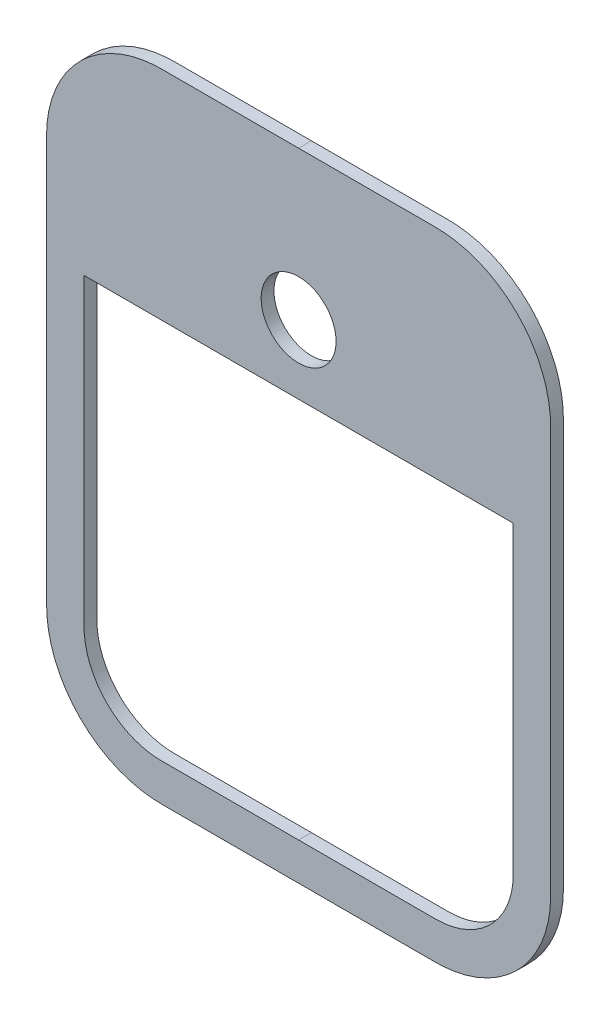
SolidWorks part; units mm, degrees
material "Фанера"
ref_plane "Front Plane" through (0, 0, 0) normal (0, 0, 1) x (1, 0, 0)
ref_plane "Top Plane" through (0, 0, 0) normal (0, 1, 0) x (1, 0, 0)
ref_plane "Right Plane" through (0, 0, 0) normal (1, 0, 0) x (0, 0, -1)
sketch "Эскиз1" plane through (0, 0, 0) normal (0, 0, 1) x (1, 0, 0)
  line L0 (-47, 88.5735) -> (47, 88.5735)
  circle A1 centre (0, 103.6369) radius 5.3081 construction
  circle A2 centre (0, 103.6369) radius 8.2
  spline S2 degree 3 poles (0, -3.0157) (10, -3.0157) (20, -3.0157) (31.6362, -3.0157) (34.9087, -2.6935) (39.6288, -1.2616) (43.9788, 1.0635) (47.7917, 4.1926) (50.9208, 8.0055) (53.2459, 12.3555) (54.6778, 17.0756) (55, 20.3481) (55, 51.6579) (55, 81.3315) (55, 112.6414) (54.6778, 115.9139) (53.2459, 120.6339) (50.9208, 124.984) (47.7917, 128.7968) (43.9788, 131.926) (39.6288, 134.2511) (34.9087, 135.6829) (31.6362, 136.0052) (20, 136.0052) (10, 136.0052) (0, 136.0052) knots 0 0 0 0 0.131833 0.131833 0.153404 0.174975 0.196546 0.218117 0.239689 0.26126 0.282831 0.304402 0.304402 0.695598 0.695598 0.717169 0.73874 0.760311 0.781883 0.803454 0.825025 0.846596 0.868167 0.868167 1 1 1 1 construction
  spline S3 degree 3 poles (0, 136.0052) (-10, 136.0052) (-20, 136.0052) (-31.6362, 136.0052) (-34.9087, 135.6829) (-39.6288, 134.2511) (-43.9788, 131.926) (-47.7917, 128.7968) (-50.9208, 124.984) (-53.2459, 120.6339) (-54.6778, 115.9139) (-55, 112.6414) (-55, 81.3315) (-55, 51.6579) (-55, 20.3481) (-54.6778, 17.0756) (-53.2459, 12.3555) (-50.9208, 8.0055) (-47.7917, 4.1926) (-43.9788, 1.0635) (-39.6288, -1.2616) (-34.9087, -2.6935) (-31.6362, -3.0157) (-20, -3.0157) (-10, -3.0157) (0, -3.0157) knots 0 0 0 0 0.131833 0.131833 0.153404 0.174975 0.196546 0.218117 0.239689 0.26126 0.282831 0.304402 0.304402 0.695598 0.695598 0.717169 0.73874 0.760311 0.781883 0.803454 0.825025 0.846596 0.868167 0.868167 1 1 1 1 construction
  spline S4 degree 1 poles (0, 136.2052) (0, -3.2157) knots 0 0 1 1 construction
  spline S5 degree 1 poles (0, -3.2157) (0, 136.2052) knots 0 0 1 1 construction
  spline S6 degree 3 poles (0, 136.2052) (-2.3704, 136.2052) (-7.1112, 136.2051) (-14.2228, 136.2054) (-20.1479, 136.2046) (-24.8907, 136.2062) (-28.4404, 136.2012) (-32.0181, 136.22) (-35.5745, 135.6656) (-39.013, 134.63) (-43.357, 132.6076) (-48.1651, 128.9623) (-51.755, 124.1125) (-53.7267, 119.7454) (-54.724, 116.2955) (-55.2324, 112.732) (-55.1913, 109.1586) (-55.2023, 105.6077) (-55.1987, 100.8653) (-55.2004, 94.94) (-55.1999, 87.8285) (-55.2001, 78.3469) (-55.2, 66.4947) (-55.2001, 54.6426) (-55.1999, 45.161) (-55.2004, 38.0495) (-55.1987, 32.1242) (-55.2023, 27.3818) (-55.1913, 23.8308) (-55.2324, 20.2575) (-54.724, 16.694) (-53.7267, 13.2441) (-51.755, 8.8769) (-48.1651, 4.0272) (-43.357, 0.3819) (-39.013, -1.6405) (-35.5745, -2.6761) (-32.0181, -3.2305) (-28.4404, -3.2117) (-24.8907, -3.2167) (-20.1479, -3.2151) (-14.2228, -3.2159) (-7.1112, -3.2156) (-2.3704, -3.2157) (0, -3.2157) knots 0 0 0 0 0.03125 0.0625 0.09375 0.109375 0.125 0.140625 0.15625 0.171875 0.1875 0.21875 0.25 0.265625 0.28125 0.296875 0.3125 0.328125 0.34375 0.375 0.40625 0.4375 0.5 0.5625 0.59375 0.625 0.65625 0.671875 0.6875 0.703125 0.71875 0.734375 0.75 0.78125 0.8125 0.828125 0.84375 0.859375 0.875 0.890625 0.90625 0.9375 0.96875 1 1 1 1
  spline S7 degree 3 poles (0, -3.2157) (2.3704, -3.2157) (7.1112, -3.2156) (14.2228, -3.2159) (20.1479, -3.2151) (24.8907, -3.2167) (28.4404, -3.2117) (32.0181, -3.2305) (35.5745, -2.6761) (39.013, -1.6405) (43.357, 0.3819) (48.1651, 4.0272) (51.755, 8.8769) (53.7267, 13.2441) (54.724, 16.694) (55.2324, 20.2575) (55.1913, 23.8308) (55.2023, 27.3818) (55.1987, 32.1242) (55.2004, 38.0495) (55.1999, 45.161) (55.2001, 54.6426) (55.2, 66.4947) (55.2001, 78.3469) (55.1999, 87.8285) (55.2004, 94.94) (55.1987, 100.8653) (55.2023, 105.6077) (55.1913, 109.1586) (55.2324, 112.732) (54.724, 116.2955) (53.7267, 119.7454) (51.755, 124.1125) (48.1651, 128.9623) (43.357, 132.6076) (39.013, 134.63) (35.5745, 135.6656) (32.0181, 136.22) (28.4404, 136.2012) (24.8907, 136.2062) (20.1479, 136.2046) (14.2228, 136.2054) (7.1112, 136.2051) (2.3704, 136.2052) (0, 136.2052) knots 0 0 0 0 0.03125 0.0625 0.09375 0.109375 0.125 0.140625 0.15625 0.171875 0.1875 0.21875 0.25 0.265625 0.28125 0.296875 0.3125 0.328125 0.34375 0.375 0.40625 0.4375 0.5 0.5625 0.59375 0.625 0.65625 0.671875 0.6875 0.703125 0.71875 0.734375 0.75 0.78125 0.8125 0.828125 0.84375 0.859375 0.875 0.890625 0.90625 0.9375 0.96875 1 1 1 1
  spline S8 degree 1 poles (0, 128.0052) (0, 4.9843) knots 0 0 1 1 construction
  spline S9 degree 1 poles (0, 4.9843) (0, 128.0052) knots 0 0 1 1 construction
  spline S10 degree 3 poles (0, 128.0052) (-2.3704, 128.0052) (-7.1113, 128.0052) (-13.0373, 128.0052) (-17.7782, 128.0052) (-20.7411, 128.0052) (-23.1118, 128.0052) (-24.8889, 128.0052) (-26.6692, 128.0052) (-28.1432, 128.0051) (-29.1936, 128.0052) (-29.6934, 128.0051) (-30.02, 128.0053) (-30.1904, 128.0046) (-30.4571, 128) (-30.8539, 127.9857) (-31.3599, 127.9543) (-31.9612, 127.8952) (-32.7609, 127.788) (-34.1451, 127.5265) (-36.0814, 126.9418) (-39.0103, 125.5784) (-42.2541, 123.1194) (-44.6763, 119.8468) (-46.0055, 116.9027) (-46.568, 114.9601) (-46.8135, 113.5726) (-46.9115, 112.7716) (-46.9636, 112.1695) (-46.9892, 111.6641) (-46.9977, 111.3153) (-46.9996, 111.1342) (-47, 111.0417) (-47, 110.8408) (-47, 110.4912) (-47, 109.9057) (-47, 109.1615) (-47, 108.2737) (-47, 107.0881) (-47, 105.0142) (-47, 102.0511) (-47, 98.4955) (-47, 94.2992) (-47, 90.6956) (-47, 85.9548) (-47, 80.6693) (-47, 73.606) (-47, 66.4947) (-47, 59.3835) (-47, 52.2722) (-47, 45.1609) (-47, 39.2349) (-47, 34.494) (-47, 30.9384) (-47, 27.9753) (-47, 25.9014) (-47, 24.7158) (-47, 23.828) (-47, 23.0837) (-47, 22.4982) (-47, 22.1486) (-47, 21.9478) (-46.9996, 21.8553) (-46.9977, 21.6741) (-46.9892, 21.3254) (-46.9636, 20.82) (-46.9115, 20.2179) (-46.8135, 19.4169) (-46.568, 18.0294) (-46.0055, 16.0868) (-44.6763, 13.1427) (-42.2541, 9.87) (-39.0103, 7.411) (-36.0814, 6.0477) (-34.1451, 5.4629) (-32.7609, 5.2015) (-31.9612, 5.0943) (-31.3599, 5.0352) (-30.8539, 5.0038) (-30.4571, 4.9895) (-30.1904, 4.9849) (-30.02, 4.9842) (-29.6934, 4.9844) (-29.1936, 4.9843) (-28.1432, 4.9843) (-26.6692, 4.9843) (-24.8889, 4.9843) (-23.1118, 4.9843) (-20.7411, 4.9843) (-17.7782, 4.9843) (-13.0373, 4.9843) (-7.1113, 4.9843) (-2.3704, 4.9843) (0, 4.9843) knots 0 0 0 0 0.03125 0.0625 0.078125 0.09375 0.101562 0.109375 0.117188 0.125 0.128906 0.130859 0.131836 0.132812 0.134766 0.136719 0.140625 0.144531 0.148438 0.15625 0.171875 0.1875 0.21875 0.25 0.265625 0.28125 0.289062 0.292969 0.296875 0.300781 0.302734 0.303711 0.304199 0.304688 0.306641 0.308594 0.3125 0.316406 0.320312 0.328125 0.34375 0.359375 0.375 0.39907 0.406882 0.4375 0.46875 0.5 0.53125 0.5625 0.59375 0.625 0.640625 0.65625 0.671875 0.679688 0.683594 0.6875 0.691406 0.693359 0.695312 0.695801 0.696289 0.697266 0.699219 0.703125 0.707031 0.710938 0.71875 0.734375 0.75 0.78125 0.8125 0.828125 0.84375 0.851562 0.855469 0.859375 0.863281 0.865234 0.867188 0.868164 0.869141 0.871094 0.875 0.882812 0.890625 0.898438 0.90625 0.921875 0.9375 0.96875 1 1 1 1
  spline S11 degree 3 poles (0, 4.9843) (2.3704, 4.9843) (7.1113, 4.9843) (13.0373, 4.9843) (17.7782, 4.9843) (20.7411, 4.9843) (23.1118, 4.9843) (24.8889, 4.9843) (26.6692, 4.9843) (28.1432, 4.9843) (29.1936, 4.9843) (29.6934, 4.9844) (30.02, 4.9842) (30.1904, 4.9849) (30.4571, 4.9895) (30.8539, 5.0038) (31.3599, 5.0352) (31.9612, 5.0943) (32.7609, 5.2015) (34.1451, 5.4629) (36.0814, 6.0477) (39.0103, 7.411) (42.2541, 9.87) (44.6763, 13.1427) (46.0055, 16.0868) (46.568, 18.0294) (46.8135, 19.4169) (46.9115, 20.2179) (46.9636, 20.82) (46.9892, 21.3254) (46.9977, 21.6741) (46.9996, 21.8553) (47, 21.9478) (47, 22.1486) (47, 22.4982) (47, 23.0837) (47, 23.828) (47, 24.7158) (47, 25.9014) (47, 27.9753) (47, 30.9384) (47, 34.494) (47, 39.2349) (47, 45.1609) (47, 52.2722) (47, 59.3835) (47, 66.4947) (47, 73.606) (47, 80.6693) (47, 85.9548) (47, 90.6956) (47, 94.2992) (47, 98.4955) (47, 102.0511) (47, 105.0142) (47, 107.0881) (47, 108.2737) (47, 109.1615) (47, 109.9057) (47, 110.4912) (47, 110.8408) (47, 111.0417) (46.9996, 111.1342) (46.9977, 111.3153) (46.9892, 111.6641) (46.9636, 112.1695) (46.9115, 112.7716) (46.8135, 113.5726) (46.568, 114.9601) (46.0055, 116.9027) (44.6763, 119.8468) (42.2541, 123.1194) (39.0103, 125.5784) (36.0814, 126.9418) (34.1451, 127.5265) (32.7609, 127.788) (31.9612, 127.8952) (31.3599, 127.9543) (30.8539, 127.9857) (30.4571, 128) (30.1904, 128.0046) (30.02, 128.0053) (29.6934, 128.0051) (29.1936, 128.0052) (28.1432, 128.0051) (26.6692, 128.0052) (24.8889, 128.0052) (23.1118, 128.0052) (20.7411, 128.0052) (17.7782, 128.0052) (13.0373, 128.0052) (7.1113, 128.0052) (2.3704, 128.0052) (0, 128.0052) knots 0 0 0 0 0.03125 0.0625 0.078125 0.09375 0.101562 0.109375 0.117188 0.125 0.128906 0.130859 0.131836 0.132812 0.134766 0.136719 0.140625 0.144531 0.148438 0.15625 0.171875 0.1875 0.21875 0.25 0.265625 0.28125 0.289062 0.292969 0.296875 0.300781 0.302734 0.303711 0.304199 0.304688 0.306641 0.308594 0.3125 0.316406 0.320312 0.328125 0.34375 0.359375 0.375 0.40625 0.4375 0.46875 0.5 0.53125 0.5625 0.593118 0.60093 0.625 0.640625 0.65625 0.671875 0.679688 0.683594 0.6875 0.691406 0.693359 0.695312 0.695801 0.696289 0.697266 0.699219 0.703125 0.707031 0.710938 0.71875 0.734375 0.75 0.78125 0.8125 0.828125 0.84375 0.851562 0.855469 0.859375 0.863281 0.865234 0.867188 0.868164 0.869141 0.871094 0.875 0.882812 0.890625 0.898438 0.90625 0.921875 0.9375 0.96875 1 1 1 1
  dimension "D1" = 16.4
  dimension "D2" = 0.2
  dimension "D3" = 8
extrude "Бобышка-Вытянуть1" add sketch "Эскиз1" along normal mid plane 2.8 contours L0 S11 S10 A2 | S6 S7 S11 S10
